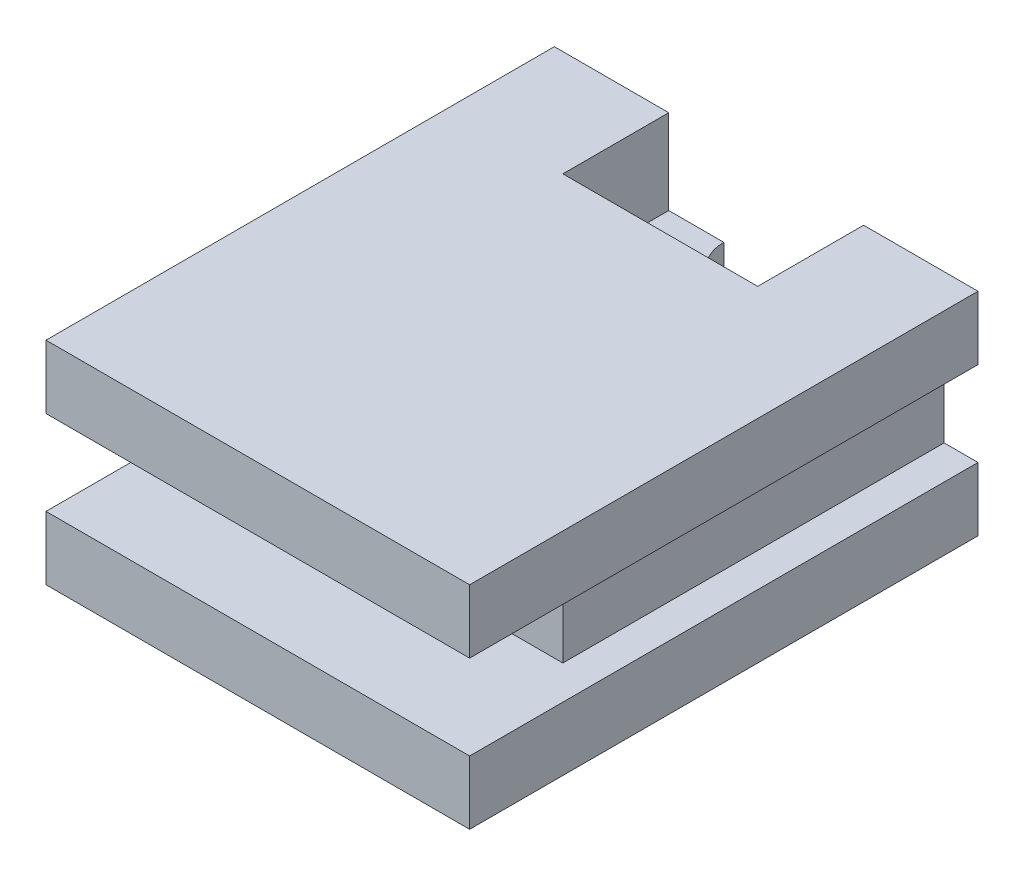
SolidWorks part; units mm, degrees
ref_plane "Спереди" through (0, 0, 0) normal (0, 0, 1) x (1, 0, 0)
ref_plane "Сверху" through (0, 0, 0) normal (0, 1, 0) x (1, 0, 0)
ref_plane "Справа" through (0, 0, 0) normal (1, 0, 0) x (0, 0, -1)
sketch "Эскиз1" plane through (0, 0, 0) normal (0, 0, 1) x (1, 0, 0)
  line L0 (-25, 0) -> (25, 0) construction
  line L1 (-25, -12.5) -> (25, -12.5)
  line L2 (-25, -12.5) -> (-25, 12.5)
  line L3 (-25, 12.5) -> (25, 12.5)
  line L4 (25, -12.5) -> (25, 12.5)
  line L5 (-25, -12.5) -> (25, 12.5) construction
  line L6 (-25, 12.5) -> (25, -12.5) construction
  line L8 (21, -5) -> (25, -5)
  line L9 (21, -5) -> (21, 5)
  line L10 (21, 5) -> (25, 5)
  line L11 (25, -5) -> (25, 5)
  line L12 (21, -5) -> (25, 5) construction
  line L13 (21, 5) -> (25, -5) construction
  line L14 (-21, -5) -> (-25, -5)
  line L15 (-21, -5) -> (-21, 5)
  line L16 (-21, 5) -> (-25, 5)
  line L17 (-25, -5) -> (-25, 5)
  line L18 (-21, -5) -> (-25, 5) construction
  line L19 (-21, 5) -> (-25, -5) construction
  point P0 (0, 0)
  point P8 (23, 0)
  point P13 (-23, 0)
  dimension "D1" = 25
  dimension "D2" = 50
  dimension "D3" = 10
  dimension "D4" = 4
extrude "Бобышка-Вытянуть1" add sketch "Эскиз1" along normal blind 60 contours L16 L15 L14 L2 L1 L4 L8 L9 L10 L3
sketch "Эскиз2" plane through (-21, 0, 0) normal (-1, 0, 0) x (0, 0, 1)
  line L0 (0, 0) -> (60, 0) construction
  line L1 (60, -5) -> (60, 5) construction
  line L2 (60, 5) -> (0, 5) construction
  line L3 (45, -5) -> (60, -5)
  line L4 (45, -5) -> (45, 5)
  line L5 (45, 5) -> (60, 5)
  line L6 (60, -5) -> (60, 5)
  line L7 (45, -5) -> (60, 5) construction
  line L8 (45, 5) -> (60, -5) construction
  point P5 (52.5, 0)
  dimension "D1" = 15
extrude "Вырез-Вытянуть1" cut sketch "Эскиз2" against normal through all
sketch "Эскиз4" plane through (0, 12.5, 0) normal (0, 1, 0) x (1, 0, 0)
  line L1 (-25, 0) -> (25, 0) construction
  circle A0 centre (0, 0) radius 5
  dimension "D1" = 10
extrude "Вырез-Вытянуть2" cut sketch "Эскиз4" against normal through all
sketch "Эскиз5" plane through (0, 12.5, 0) normal (0, 1, 0) x (1, 0, 0)
  line L1 (-11.5, -12.5) -> (11.5, -12.5)
  line L2 (-11.5, -12.5) -> (-11.5, 12.5)
  line L3 (-11.5, 12.5) -> (11.5, 12.5)
  line L4 (11.5, -12.5) -> (11.5, 12.5)
  line L5 (-11.5, -12.5) -> (11.5, 12.5) construction
  line L6 (-11.5, 12.5) -> (11.5, -12.5) construction
  point P0 (0, 0)
  dimension "D1" = 25
  dimension "D2" = 23
extrude "Вырез-Вытянуть3" cut sketch "Эскиз5" against normal blind 10
